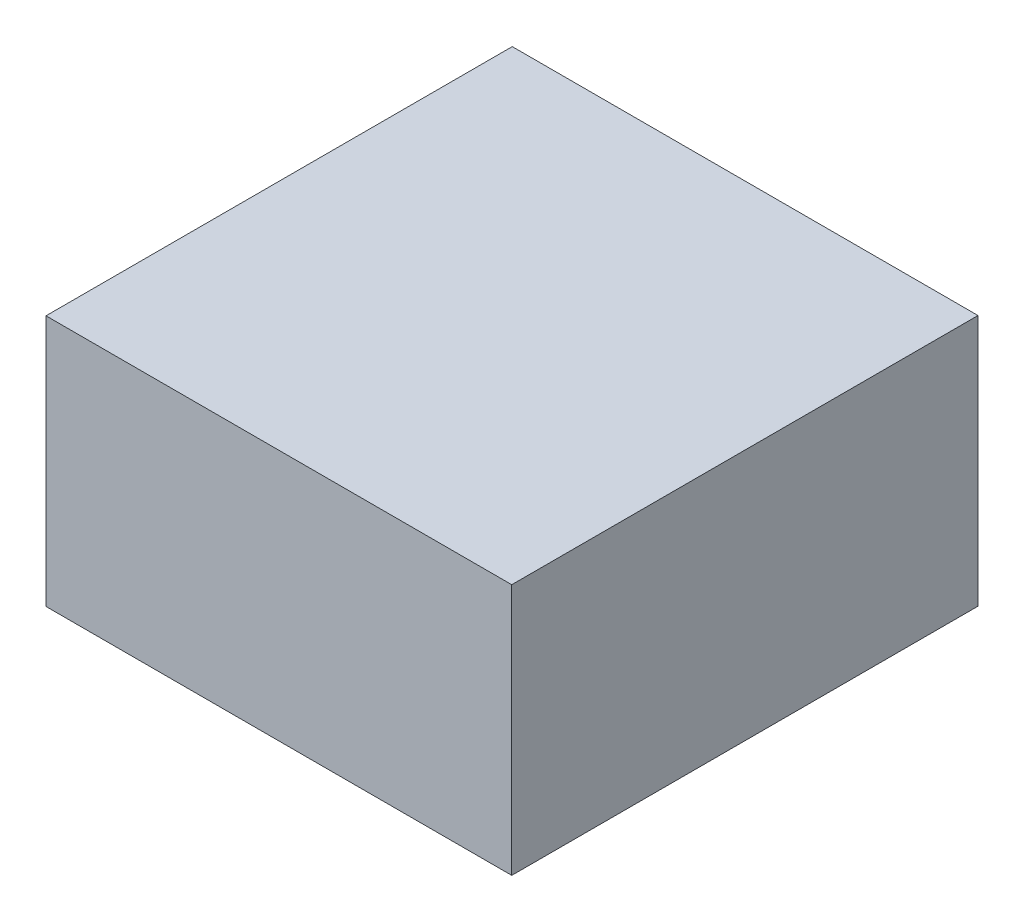
SolidWorks part; units mm, degrees
ref_plane "Front Plane" through (0, 0, 0) normal (0, 0, 1) x (1, 0, 0)
ref_plane "Top Plane" through (0, 0, 0) normal (0, 1, 0) x (1, 0, 0)
ref_plane "Right Plane" through (0, 0, 0) normal (1, 0, 0) x (0, 0, -1)
sketch "Sketch1" plane through (0, 0, 0) normal (0, 1, 0) x (1, 0, 0)
  line L1 (0, 0) -> (241.3, 0)
  line L2 (0, 0) -> (0, 117.602)
  line L3 (0, 117.602) -> (241.3, 117.602)
  line L4 (241.3, 0) -> (241.3, 117.602)
  dimension "D1" = 241.3
  dimension "D2" = 117.602
extrude "Boss-Extrude1" add sketch "Sketch1" along normal blind 63.5
sketch "Sketch2" plane through (0, 63.5, 0) normal (0, 1, 0) x (1, 0, 0)
  line L2 (117.475, 117.602) -> (117.475, 0)
  line L3 (117.475, 0) -> (241.3, 0)
  line L4 (241.3, 117.602) -> (241.3, 0)
  line L5 (241.3, 117.602) -> (0, 117.602) construction
  line L6 (117.475, 117.602) -> (241.3, 117.602)
  dimension "D1" = 123.825
extrude "Cut-Extrude1" cut sketch "Sketch2" against normal through all
